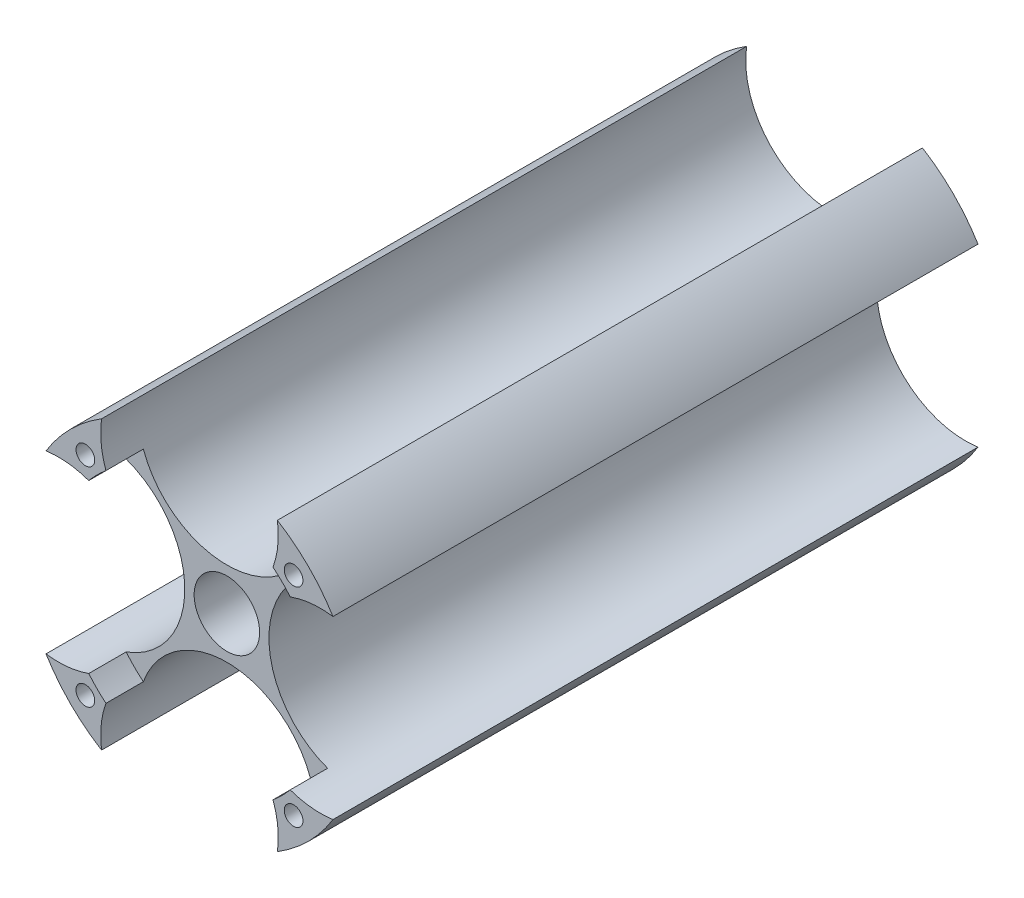
SolidWorks part; units mm, degrees
material "ABS"
ref_plane "Спереди" through (0, 0, 0) normal (0, 0, 1) x (1, 0, 0)
ref_plane "Сверху" through (0, 0, 0) normal (0, 1, 0) x (1, 0, 0)
ref_plane "Справа" through (0, 0, 0) normal (1, 0, 0) x (0, 0, -1)
sketch "Эскиз1" plane through (0, 0, 0) normal (0, 0, 1) x (1, 0, 0)
  line L0 (0, 0) -> (0, -18) construction
  line L1 (0, 0) -> (0, 18) construction
  line L2 (0, 0) -> (-18.5984, 18.5984) construction
  line L3 (0, 0) -> (-14, 0) construction
  circle A0 centre (0, 0) radius 18
  circle A1 centre (0, -14) radius 9.5
  circle A2 centre (-14, 0) radius 9.5
  circle A3 centre (0, 14) radius 9.5
  circle A7 centre (0, 0) radius 3.5
  circle A8 centre (14, 0) radius 9.5
  circle A9 centre (-11.1369, 11.1369) radius 1
  circle A10 centre (11.1369, 11.1369) radius 1
  circle A11 centre (11.1369, -11.1369) radius 1
  circle A12 centre (-11.1369, -11.1369) radius 1
  point P13 (0, 0)
  point P20 (0, 0)
  point P28 (0, 0)
  dimension "D1" = 19
  dimension "D4" = 36
  dimension "D5" = 45
  dimension "D7" = 7
  dimension "D6" = 2
  dimension "D2" = 14
  dimension "D8" = 15.75
  dimension "D3" = 4
  dimension "D9" = 4
extrude "Бобышка-Вытянуть1" add sketch "Эскиз1" along normal blind 65
sketch "Эскиз2" plane through (0, 0, 65) normal (0, 0, 1) x (1, 0, 0)
  circle A0 centre (0, 0) radius 14
  circle A1 centre (14, 0) radius 9.5
  circle A2 centre (14, 0) radius 9.5
  circle A3 centre (0, 14) radius 9.5
  circle A4 centre (0, 14) radius 9.5
  circle A5 centre (-14, 0) radius 9.5
  circle A6 centre (-14, 0) radius 9.5
  circle A7 centre (0, -14) radius 9.5
  circle A8 centre (0, -14) radius 9.5
  circle A9 centre (0, 0) radius 18
  circle A10 centre (0, 0) radius 18
  circle A11 centre (-11.1369, -11.1369) radius 1
  circle A12 centre (-11.1369, -11.1369) radius 1
  circle A13 centre (11.1369, -11.1369) radius 1
  circle A14 centre (11.1369, -11.1369) radius 1
  circle A15 centre (11.1369, 11.1369) radius 1
  circle A16 centre (11.1369, 11.1369) radius 1
  circle A17 centre (-11.1369, 11.1369) radius 1
  circle A18 centre (-11.1369, 11.1369) radius 1
  circle A19 centre (0, 0) radius 3.5
  circle A20 centre (0, 0) radius 3.5
  circle M11 centre (-11.1369, -11.1369) radius 1
  circle M12 centre (11.1369, -11.1369) radius 1
  circle M13 centre (11.1369, 11.1369) radius 1
  circle M14 centre (-11.1369, 11.1369) radius 1
  arc M15 (15.3482, -9.4038) -> (15.3482, 9.4038) centre (14, 0) cw
  arc M16 (15.3482, 9.4038) -> (9.4038, 15.3482) centre (0, 0) ccw
  arc M17 (9.4038, 15.3482) -> (-9.4038, 15.3482) centre (0, 14) cw
  arc M18 (-9.4038, 15.3482) -> (-15.3482, 9.4038) centre (0, 0) ccw
  arc M19 (-15.3482, 9.4038) -> (-15.3482, -9.4038) centre (-14, 0) cw
  arc M20 (-15.3482, -9.4038) -> (-9.4038, -15.3482) centre (0, 0) ccw
  arc M21 (-9.4038, -15.3482) -> (9.4038, -15.3482) centre (0, -14) cw
  arc M22 (9.4038, -15.3482) -> (15.3482, -9.4038) centre (0, 0) ccw
  dimension "D1" = 0
  dimension "D2" = 0
  dimension "D3" = 0
  dimension "D4" = 0
  dimension "D5" = 0
  dimension "D6" = 0
  dimension "D7" = 0
  dimension "D8" = 0
  dimension "D9" = 0
  dimension "D10" = 0
extrude "Бобышка-Вытянуть2" add sketch "Эскиз2" along normal blind 4 contours A0 M19 M20 M21 M11 | A0 M21 M22 M15 M12 | A0 M15 M16 M17 M13 | A0 M17 M18 M19 M14
